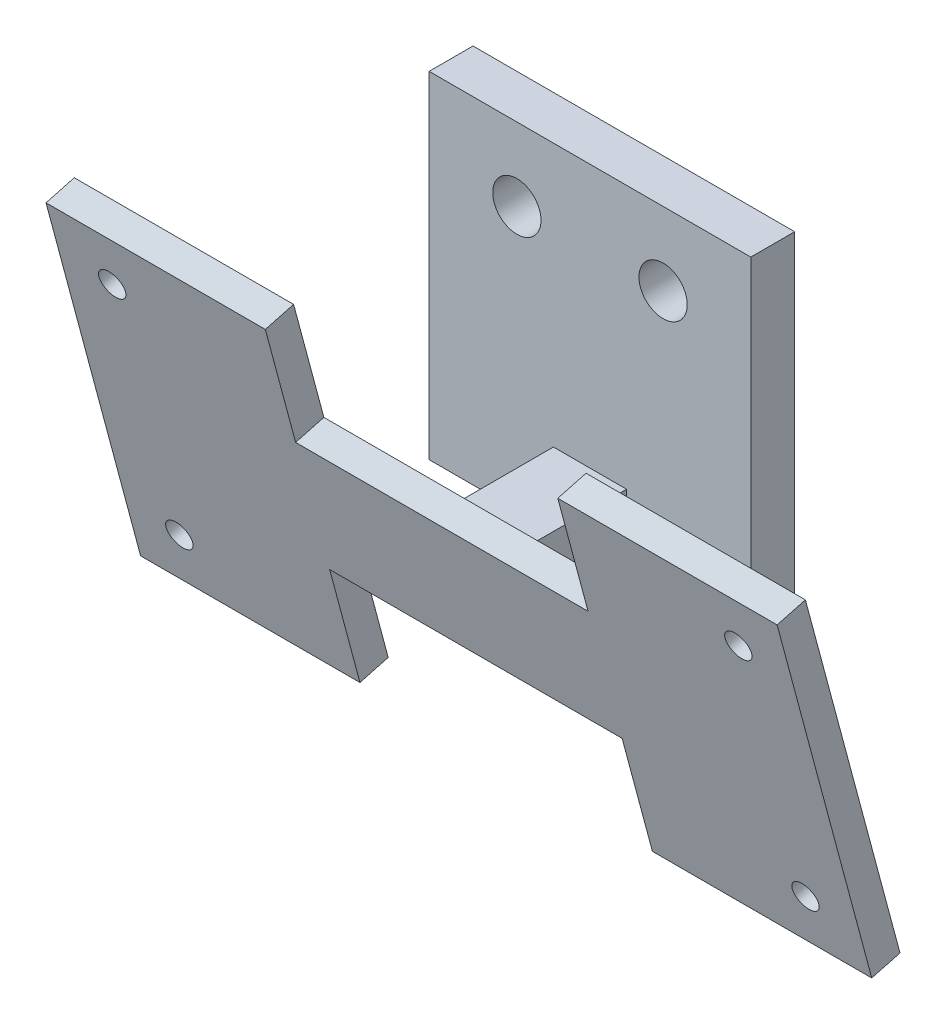
SolidWorks part; units mm, degrees
ref_plane "前视基准面" through (0, 0, 0) normal (0, 0, 1) x (1, 0, 0)
ref_plane "上视基准面" through (0, 0, 0) normal (0, 1, 0) x (1, 0, 0)
ref_plane "右视基准面" through (0, 0, 0) normal (1, 0, 0) x (0, 0, -1)
sketch "草图1" plane through (0, 0, 0) normal (0, 0, 1) x (1, 0, 0)
  line L0 (0, -3.7171) -> (0, 3.7171) construction
  line L2 (-11, -5) -> (11, -5)
  line L3 (-11, -5) -> (-11, 5)
  line L4 (-11, 5) -> (11, 5)
  line L5 (11, -5) -> (11, 5)
  line L6 (-11, -5) -> (11, 5) construction
  line L7 (-11, 5) -> (11, -5) construction
  circle A0 centre (-5, 0) radius 1.65
  circle A1 centre (5, 0) radius 1.65
  point P6 (0, 0)
  dimension "D1" = 10
  dimension "D2" = 3.3
  dimension "D3" = 22
  dimension "D4" = 10
extrude "凸台-拉伸1" add sketch "草图1" along normal blind 3
sketch "草图2" plane through (0, -5, 0) normal (0, -1, 0) x (1, 0, 0)
  line L1 (-11, 3) -> (11, 3)
  line L2 (-11, 3) -> (-11, 0)
  line L3 (-11, 0) -> (11, 0)
  line L4 (11, 3) -> (11, 0)
extrude "凸台-拉伸2" add sketch "草图2" along normal blind 13
sketch "草图4" plane through (0, 0, 3) normal (0, 0, 1) x (1, 0, 0)
  line L0 (11, -18) -> (-11, -18) construction
  line L1 (-2.5, -13) -> (2.5, -13)
  line L2 (-2.5, -13) -> (-2.5, -18)
  line L3 (-2.5, -18) -> (2.5, -18)
  line L4 (2.5, -13) -> (2.5, -18)
  line L5 (-2.5, -13) -> (2.5, -18) construction
  line L6 (-2.5, -18) -> (2.5, -13) construction
  point P0 (0, -15.5)
  dimension "D1" = 5
  dimension "D2" = 5
extrude "凸台-拉伸3" add sketch "草图4" along normal blind 8
ref_plane "基准面1" through (0, 0, 0) normal (-1, 0, 0) x (0, 0, 1)
sketch "草图6" plane through (0, 0, 0) normal (-1, 0, 0) x (0, 0, 1)
  line L4 (6.7988, -27.3153) -> (13.2693, -3.1671)
  line L5 (6.7988, -27.3153) -> (8.7307, -27.8329)
  line L7 (13.2693, -3.1671) -> (15.2012, -3.6847)
  line L8 (8.7307, -27.8329) -> (15.2012, -3.6847)
  line L9 (6.7988, -27.3153) -> (15.2012, -3.6847) construction
  line L10 (13.2693, -3.1671) -> (8.7307, -27.8329) construction
  line L11 (11, -13) -> (11, -18) construction
  point P1 (11, -15.5)
  dimension "D1" = 15
  dimension "D2" = 2
  dimension "D3" = 25
extrude "凸台-拉伸4" add sketch "草图6" along normal mid plane 50
sketch "草图7" plane through (0, -4.0471, 15.1041) normal (0, -0.2588, 0.9659) x (1, 0, 0)
  line L0 (0, -8.3606) -> (0, 8.3606) construction
  line L1 (-25, -12.1248) -> (15.1234, -12.1248) construction
  line L2 (-25, -24.6248) -> (-25, 0.3752) construction
  circle A0 centre (-21.41, -3.2548) radius 0.91
  circle A1 centre (21.41, -3.2548) radius 0.91
  circle A2 centre (21.41, -20.9948) radius 0.91
  circle A3 centre (-21.41, -20.9948) radius 0.91
  dimension "D1" = 42.82
  dimension "D2" = 1.82
  dimension "D3" = 17.74
extrude "切除-拉伸1" cut sketch "草图7" against normal blind 30
sketch "草图8" plane through (0, -4.0471, 15.1041) normal (0, -0.2588, 0.9659) x (1, 0, 0)
  line L0 (-10, -7.6248) -> (-10, 0.3752)
  line L1 (-10, -7.6248) -> (10, -7.6248)
  line L2 (-10, 0.3752) -> (10, 0.3752)
  line L3 (10, -7.6248) -> (10, 0.3752)
  line L4 (-10, -7.6248) -> (10, 0.3752) construction
  line L5 (-10, 0.3752) -> (10, -7.6248) construction
  line L6 (-25, -12.1248) -> (-13.5997, -12.1248) construction
  line L7 (-25, -24.6248) -> (-25, 0.3752) construction
  line L8 (-10, -24.6248) -> (10, -16.6248) construction
  line L9 (-10, -16.6248) -> (10, -24.6248) construction
  line L10 (10, -16.6248) -> (10, -24.6248)
  line L11 (-10, -24.6248) -> (10, -24.6248)
  line L12 (-10, -16.6248) -> (10, -16.6248)
  line L13 (-10, -16.6248) -> (-10, -24.6248)
  point P1 (0, -3.6248)
  point P14 (0, -20.6248)
  dimension "D1" = 8
  dimension "D2" = 20
extrude "切除-拉伸2" cut sketch "草图8" against normal blind 5
